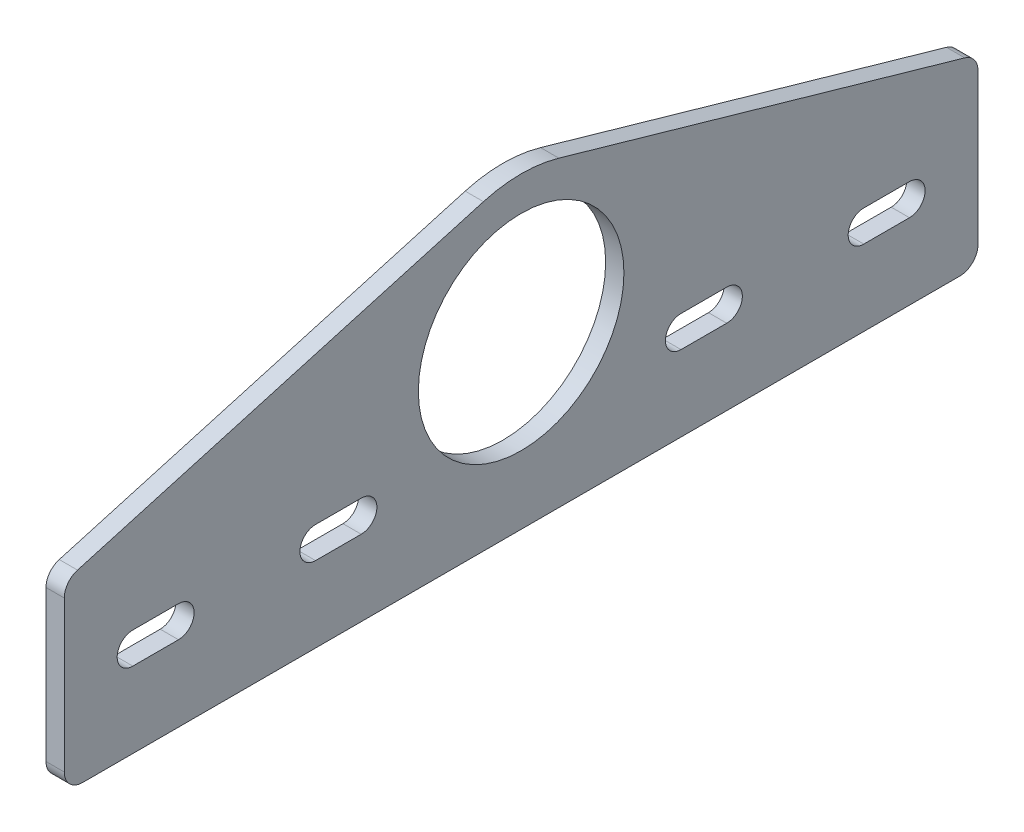
SolidWorks part; units mm, degrees
ref_plane "Front" through (0, 0, 0) normal (0, 0, 1) x (1, 0, 0)
ref_plane "Top" through (0, 0, 0) normal (0, 1, 0) x (1, 0, 0)
ref_plane "Right" through (0, 0, 0) normal (1, 0, 0) x (0, 0, -1)
sketch "Sketch1" plane through (0, 0, 0) normal (1, 0, 0) x (0, 0, -1)
  line L0 (381, -23.749) -> (-381, -23.749) construction
  line L1 (-63.5, -23.749) -> (63.5, -23.749)
  line L2 (-63.5, -23.749) -> (-63.5, 1.651)
  line L4 (63.5, -23.749) -> (63.5, 1.651)
  line L6 (381, 1.651) -> (370.3687, 1.651) construction
  line L8 (63.5, 1.651) -> (5.2388, 18.3155)
  line L9 (-5.2388, 18.3155) -> (-63.5, 1.651)
  circle A1 centre (-50.8, -11.049) radius 2.0701 construction
  circle A2 centre (50.8, -11.049) radius 2.0701 construction
  arc A3 (5.2388, 18.3155) -> (-5.2388, 18.3155) centre (0, 0) ccw
  point P0 (0, 0)
  dimension "D1" = 12.7
  dimension "D2" = 12.7
  dimension "D3" = 38.1
extrude "Boss-Extrude1" add sketch "Sketch1" along normal blind 2.54 contours L4 L8 A3 L9 L2 L1
sketch "Sketch3" plane through (0, 0, 0) normal (-1, 0, 0) x (0, 0, 1)
  line L0 (-53.975, -11.049) -> (-47.625, -11.049) construction
  line L1 (-53.975, -8.8773) -> (-47.625, -8.8773)
  line L2 (-53.975, -13.2207) -> (-47.625, -13.2207)
  line L3 (-28.575, -11.049) -> (-22.225, -11.049) construction
  line L6 (-28.575, -8.8773) -> (-22.225, -8.8773)
  line L9 (-28.575, -13.2207) -> (-22.225, -13.2207)
  line L12 (-63.5, -23.749) -> (-63.5, 1.651) construction
  line L13 (63.5, -23.749) -> (-63.5, -23.749) construction
  line L17 (22.225, -11.049) -> (28.575, -11.049) construction
  line L18 (22.225, -8.8773) -> (28.575, -8.8773)
  line L19 (22.225, -13.2207) -> (28.575, -13.2207)
  line L20 (47.625, -11.049) -> (53.975, -11.049) construction
  line L21 (47.625, -8.8773) -> (53.975, -8.8773)
  line L22 (47.625, -13.2207) -> (53.975, -13.2207)
  line L53 (-3.175, -11.049) -> (3.175, -11.049) construction
  line L54 (-3.175, -8.8773) -> (3.175, -8.8773)
  line L55 (-3.175, -13.2207) -> (3.175, -13.2207)
  line L56 (-3.175, -11.049) -> (3.175, -11.049) construction
  line L57 (-3.175, -8.8773) -> (3.175, -8.8773)
  line L58 (-3.175, -13.2207) -> (3.175, -13.2207)
  circle A0 centre (0, 0) radius 14.2875
  arc A6 (-53.975, -8.8773) -> (-53.975, -13.2207) centre (-53.975, -11.049) ccw
  arc A7 (-47.625, -13.2207) -> (-47.625, -8.8773) centre (-47.625, -11.049) ccw
  arc A10 (-28.575, -8.8773) -> (-28.575, -13.2207) centre (-28.575, -11.049) ccw
  arc A11 (-22.225, -13.2207) -> (-22.225, -8.8773) centre (-22.225, -11.049) ccw
  arc A14 (22.225, -8.8773) -> (22.225, -13.2207) centre (22.225, -11.049) ccw
  arc A15 (28.575, -13.2207) -> (28.575, -8.8773) centre (28.575, -11.049) ccw
  arc A16 (47.625, -8.8773) -> (47.625, -13.2207) centre (47.625, -11.049) ccw
  arc A17 (53.975, -13.2207) -> (53.975, -8.8773) centre (53.975, -11.049) ccw
  arc A40 (-3.175, -8.8773) -> (-3.175, -13.2207) centre (-3.175, -11.049) ccw
  arc A41 (3.175, -13.2207) -> (3.175, -8.8773) centre (3.175, -11.049) ccw
  point P3 (0, 0)
  point P4 (0, 0)
  point P5 (0, 0)
  point P9 (-50.8, -11.049)
  point P18 (-25.4, -11.049)
  point P25 (0, -11.049)
  point P32 (25.4, -11.049)
  point P43 (50.8, -11.049)
  point P50 (0, -11.049)
  point P57 (0, -11.049)
  point P64 (0, -11.049)
  point P71 (-3.1421, -7.4491)
  point P78 (-3.1421, -7.4491)
  point P85 (-3.1421, -12.6365)
  point P92 (-3.1421, -12.6365)
  point P99 (0, -12.6365)
  point P106 (0, -12.6365)
  point P113 (0, -11.049)
  point P120 (0, -11.049)
  point P127 (0, -11.049)
  dimension "D1" = 12.7
  dimension "D6" = 28.575
  dimension "D2" = 4.3434
  dimension "D3" = 12.7
  dimension "D4" = 6.35
  dimension "D5" = 5
extrude "Cut-Extrude1" cut sketch "Sketch3" against normal through all
fillet "Fillet1" radius 2.54 4 edges at (1.27, 1.651, 63.5) (1.27, -23.749, 63.5) (1.27, -23.749, -63.5) (1.27, 1.651, -63.5)
